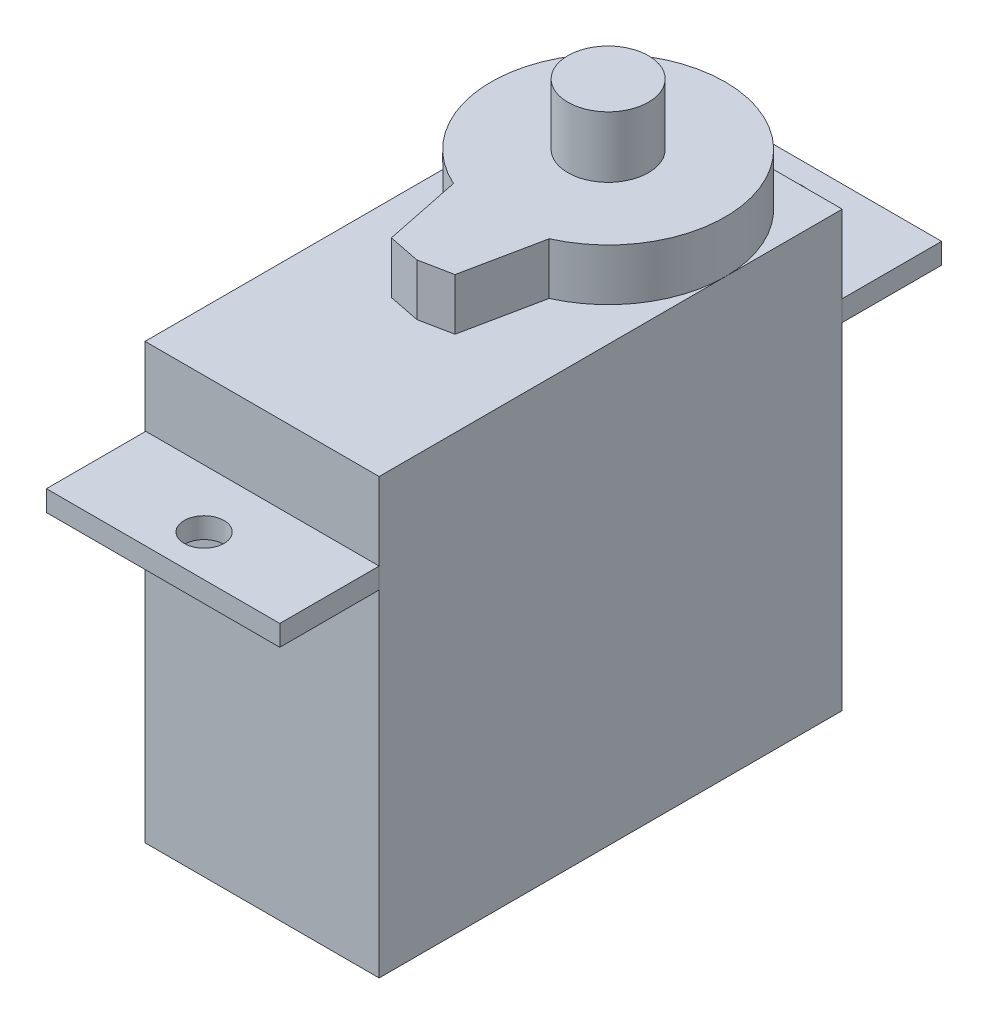
SolidWorks part; units mm, degrees
material "HS 55"
ref_plane "Front Plane" through (0, 0, 0) normal (0, 0, 1) x (1, 0, 0)
ref_plane "Top Plane" through (0, 0, 0) normal (0, 1, 0) x (1, 0, 0)
ref_plane "Right Plane" through (0, 0, 0) normal (1, 0, 0) x (0, 0, -1)
sketch "Sketch1" plane through (0, 0, 0) normal (0, 1, 0) x (1, 0, 0)
  line L0 (0, 11.375) -> (0, -11.375) construction
  line L1 (5.75, -11.375) -> (-5.75, -11.375)
  line L2 (5.75, -11.375) -> (5.75, 11.375)
  line L3 (5.75, 11.375) -> (-5.75, 11.375)
  line L4 (-5.75, -11.375) -> (-5.75, 11.375)
  line L5 (-5.75, 0) -> (5.75, 0) construction
  point P0 (0, 0)
  dimension "D1" = 22.75
  dimension "D2" = 11.5
extrude "Boss-Extrude1" add sketch "Sketch1" along normal blind 23.876
ref_plane "Plane1" through (0, 16.51, 0) normal (0, 1, 0) x (-1, 0, 0)
sketch "Sketch2" plane through (0, 16.51, 0) normal (0, 1, 0) x (-1, 0, 0)
  line L0 (-10.1754, 0) -> (12.5656, 0) construction
  line L1 (-5.75, -11.375) -> (5.715, -11.375)
  line L2 (-5.75, -11.375) -> (-5.75, -16.256)
  line L3 (-5.75, -16.256) -> (5.715, -16.256)
  line L4 (5.715, -11.375) -> (5.715, -16.256)
  line L5 (5.715, 11.375) -> (5.715, 16.256)
  line L6 (-5.75, 16.256) -> (5.715, 16.256)
  line L7 (-5.75, 11.375) -> (-5.75, 16.256)
  line L8 (-5.75, 11.375) -> (5.715, 11.375)
  circle A0 centre (0, 14.224) radius 0.9779
  circle A1 centre (0, -14.224) radius 0.9779
  dimension "D2" = 28.448
  dimension "D3" = 1.9558
  dimension "D1" = 32.512
extrude "Boss-Extrude2" add sketch "Sketch2" along normal blind 1.016 separate body
sketch "Sketch3" plane through (0, 23.876, 0) normal (0, 1, 0) x (1, 0, 0)
  line L0 (5.75, -11.375) -> (5.75, 11.375) construction
  line L2 (-5.715, 11.375) -> (5.75, 11.375) construction
  line L3 (-5.75, 11.375) -> (-5.75, -11.375) construction
  line L4 (1.5625, -3.4599) -> (0, -3.7724)
  line L5 (0, 0) -> (0, 3.951) construction
  line L6 (-1.5625, -3.4599) -> (0, -3.7724)
  line L7 (-5.75, 5.625) -> (-5.75, -11.375)
  line L8 (-5.75, -11.375) -> (5.75, -11.375)
  line L9 (5.75, -11.375) -> (5.75, 5.625)
  line L10 (5.75, 5.625) -> (5.75, 11.375)
  line L11 (5.75, 11.375) -> (0, 11.375)
  line L12 (0, 11.375) -> (-5.75, 11.375)
  line L13 (-5.75, 11.375) -> (-5.75, 5.625)
  arc A0 (2.3511, 0.3777) -> (-2.3511, 0.3777) centre (0, 5.625) ccw
  spline S0 degree 1 poles (2.3511, 0.3777) (1.5625, -3.4599) knots 0 0 1 1
  spline S1 degree 1 poles (-2.3511, 0.3777) (-1.5625, -3.4599) knots 0 0 1 1
  line M6 (-5.75, 11.375) -> (-5.75, -11.375)
  line M7 (-5.75, -11.375) -> (5.75, -11.375)
  line M8 (5.75, -11.375) -> (5.75, 11.375)
  line M9 (5.75, 11.375) -> (-5.75, 11.375)
extrude "Cut-Extrude2" cut sketch "Sketch3" against normal blind 2.54 contours S1 A0 S0 L4 L6 M6 M7 M8 | A0 M8 M9 | A0 M9 M6
sketch "Sketch4" plane through (0, 23.876, 0) normal (0, 1, 0) x (1, 0, 0)
  circle A0 centre (0, 5.625) radius 1.9812
  dimension "D1" = 3.9624
extrude "Boss-Extrude3" add sketch "Sketch4" along normal blind 3
